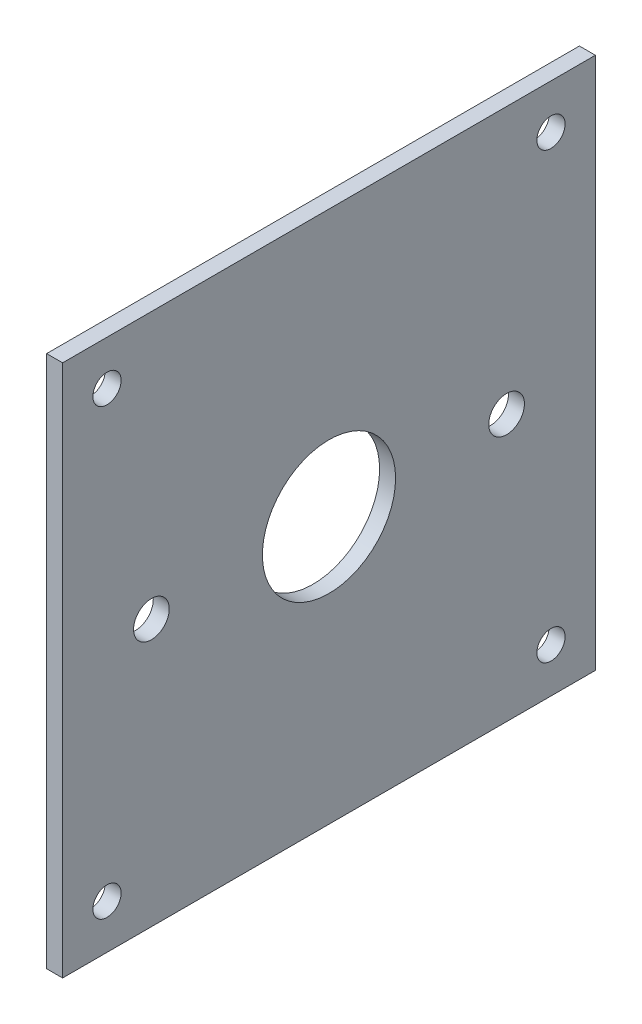
SolidWorks part; units mm, degrees
ref_plane "Front Plane" through (0, 0, 0) normal (0, 0, 1) x (1, 0, 0)
ref_plane "Top Plane" through (0, 0, 0) normal (0, 1, 0) x (1, 0, 0)
ref_plane "Right Plane" through (0, 0, 0) normal (1, 0, 0) x (0, 0, -1)
sketch "Sketch1" plane through (0, 0, 0) normal (1, 0, 0) x (0, 0, -1)
  line L0 (38.1, 38.1) -> (38.1, -38.1)
  line L1 (38.1, -38.1) -> (-38.1, -38.1)
  line L2 (-38.1, -38.1) -> (-38.1, 38.1)
  line L3 (-38.1, 38.1) -> (38.1, 38.1)
  circle A0 centre (-25.4, 0) radius 2.5527
  circle A1 centre (-31.75, 31.75) radius 2.0193
  circle A2 centre (0, 0) radius 9.525
  circle A3 centre (25.4, 0) radius 2.5527
  circle A4 centre (31.75, 31.75) radius 2.0193
  circle A5 centre (31.75, -31.75) radius 2.0193
  circle A6 centre (-31.75, -31.75) radius 2.0193
  dimension "D15" = 4.0386
  dimension "D17" = 5.1054
  dimension "D18" = 4.0386
  dimension "D19" = 4.0386
  dimension "D20" = 19.05
  dimension "D21" = 5.1054
  dimension "D22" = 4.0386
  dimension "D1" = 76.2
  dimension "D2" = 38.1
  dimension "D3" = 6.35
  dimension "D4" = 69.85
  dimension "D5" = 6.35
  dimension "D6" = 38.1
  dimension "D7" = 69.85
  dimension "D8" = 6.35
  dimension "D9" = 6.35
  dimension "D10" = 38.1
  dimension "D11" = 38.1
  dimension "D12" = 38.1
  dimension "D13" = 6.35
  dimension "D14" = 69.85
  dimension "D16" = 76.2
extrude "Boss-Extrude1" add sketch "Sketch1" along normal blind 2.286
